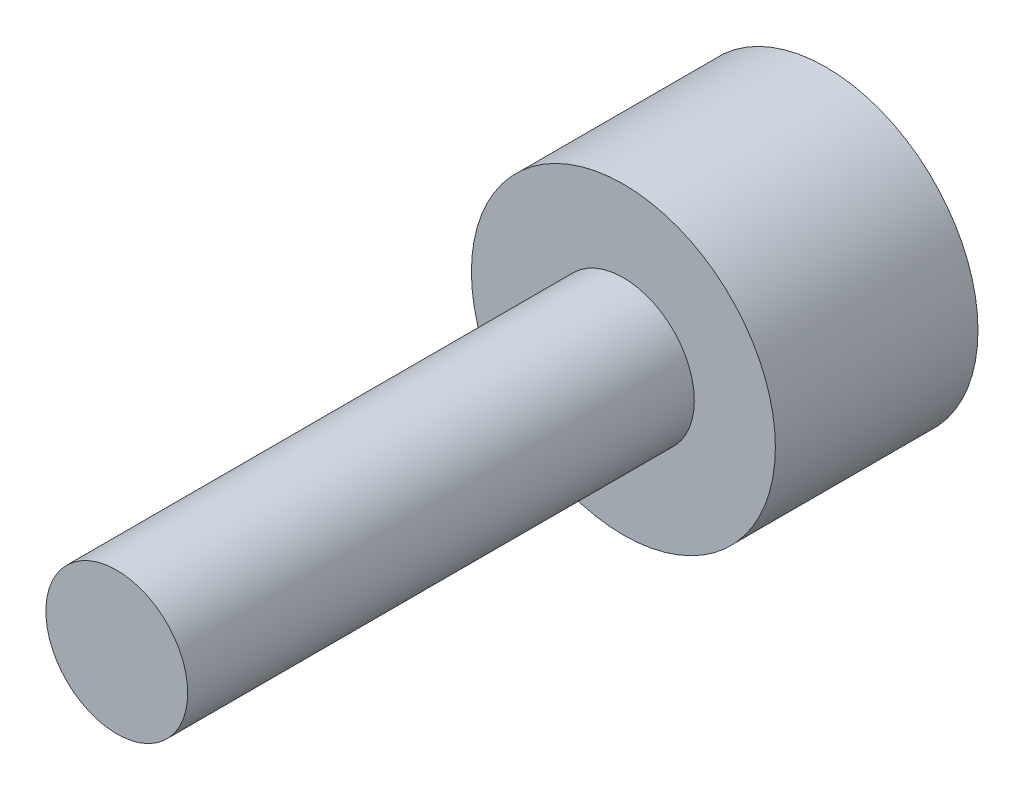
SolidWorks part; units mm, degrees
ref_plane "Front Plane" through (0, 0, 0) normal (0, 0, 1) x (1, 0, 0)
ref_plane "Top Plane" through (0, 0, 0) normal (0, 1, 0) x (1, 0, 0)
ref_plane "Right Plane" through (0, 0, 0) normal (1, 0, 0) x (0, 0, -1)
sketch "Sketch1" plane through (0, 0, 0) normal (0, 0, 1) x (1, 0, 0)
  circle A0 centre (0, 0) radius 7.5
  dimension "D1" = 15
extrude "Boss-Extrude1" add sketch "Sketch1" along normal blind 10
sketch "Sketch2" plane through (0, 0, 10) normal (0, 0, 1) x (1, 0, 0)
  circle A0 centre (0, 0) radius 3.5
  dimension "D1" = 7
extrude "Cut-Extrude1" cut sketch "Sketch2" against normal blind 10
sketch "Sketch3" plane through (0, 0, 10) normal (0, 0, 1) x (1, 0, 0)
  circle A0 centre (0, 0) radius 3.5
extrude "Boss-Extrude2" add sketch "Sketch3" along normal blind 25 separate body
